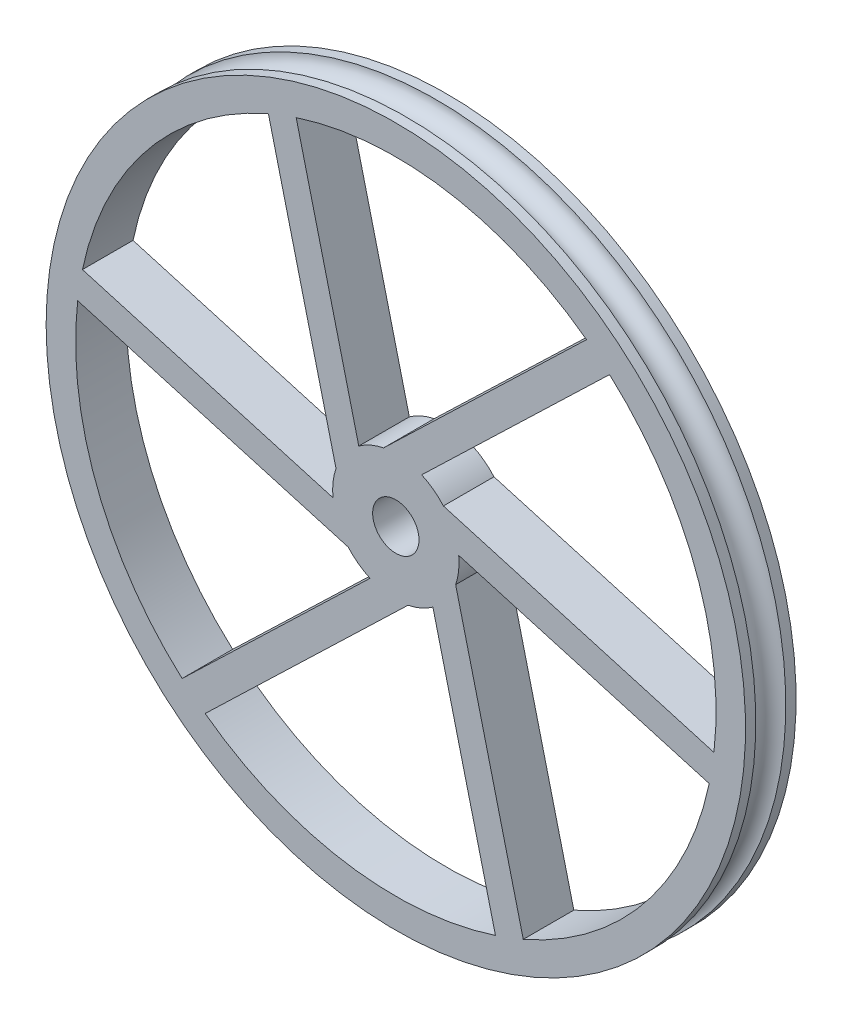
SolidWorks part; units mm, degrees
ref_plane "Front Plane" through (0, 0, 0) normal (0, 0, 1) x (1, 0, 0)
ref_plane "Top Plane" through (0, 0, 0) normal (0, 1, 0) x (1, 0, 0)
ref_plane "Right Plane" through (0, 0, 0) normal (1, 0, 0) x (0, 0, -1)
sketch "Sketch2" plane through (0, 0, 0) normal (0, 1, 0) x (1, 0, 0)
  line L0 (41.5, -1.78) -> (41.5, -3)
  line L1 (38, 3) -> (41.5, 3)
  line L2 (38, 3) -> (38, -3)
  line L3 (38, -3) -> (41.5, -3)
  line L4 (41.5, 3) -> (41.5, 1.78)
  line L5 (0, 19.9254) -> (0, -18.4403) construction
  arc A0 (41.5, 1.78) -> (41.5, -1.78) centre (41.5, 0) ccw
  point P4 (38, 0)
  dimension "D1" = 1.78
  dimension "D2" = 3.5
  dimension "D3" = 6
  dimension "D4" = 38
revolve "rim" add sketch "Sketch2" angle 360 about L5
sketch "Sketch3" plane through (0, 0, 0) normal (0, 0, 1) x (1, 0, 0)
  circle A0 centre (0, 0) radius 7.5
  dimension "D1" = 15
extrude "center" add sketch "Sketch3" along normal up to surface and the other way up to surface separate body up to face at (-41.5, 0, 3) other way up to face at (-38, 0, -3)
sketch "Sketch4" plane through (0, 0, 3) normal (0, 0, 1) x (1, 0, 0)
  line L0 (-1.4541, 7.3577) -> (23.0493, 30.9286)
  line L1 (23.0493, 30.9286) -> (25.4757, 28.4061)
  line L2 (25.4757, 28.4061) -> (3.0627, 6.8461)
  line L3 (-1.4541, 7.3577) -> (3.0627, 6.8461)
  line L4 (5.6449, 4.9381) -> (38.3095, -4.497)
  line L5 (38.3095, -4.497) -> (37.3383, -7.8595)
  line L6 (37.3383, -7.8595) -> (7.4603, 0.7707)
  line L7 (5.6449, 4.9381) -> (7.4603, 0.7707)
  line L8 (7.099, -2.4196) -> (15.2603, -35.4255)
  line L9 (15.2603, -35.4255) -> (11.8626, -36.2657)
  line L10 (11.8626, -36.2657) -> (4.3976, -6.0755)
  line L11 (7.099, -2.4196) -> (4.3976, -6.0755)
  line L12 (1.4541, -7.3577) -> (-23.0493, -30.9286)
  line L13 (-23.0493, -30.9286) -> (-25.4757, -28.4061)
  line L14 (-25.4757, -28.4061) -> (-3.0627, -6.8461)
  line L15 (1.4541, -7.3577) -> (-3.0627, -6.8461)
  line L16 (-5.6449, -4.9381) -> (-38.3095, 4.497)
  line L17 (-38.3095, 4.497) -> (-37.3383, 7.8595)
  line L18 (-37.3383, 7.8595) -> (-7.4603, -0.7707)
  line L19 (-5.6449, -4.9381) -> (-7.4603, -0.7707)
  line L20 (-7.099, 2.4196) -> (-15.2603, 35.4255)
  line L21 (-15.2603, 35.4255) -> (-11.8626, 36.2657)
  line L22 (-11.8626, 36.2657) -> (-4.3976, 6.0755)
  line L23 (-7.099, 2.4196) -> (-4.3976, 6.0755)
  circle A0 centre (0, 0) radius 7.5 construction
  point P30 (0, 0)
  dimension "D2" = 3.5
  dimension "D3" = 34
  dimension "D1" = 6
extrude "spokes" add sketch "Sketch4" against normal up to surface (6 mm away) up to face at (-38, 0, -3)
sketch "Sketch5" plane through (0, 0, 3) normal (0, 0, 1) x (1, 0, 0)
  circle A0 centre (0, 0) radius 2.75
  dimension "D1" = 5.5
extrude "hole" cut sketch "Sketch5" against normal up to surface (6 mm away) up to face at (1.3911, 21.1056, -3)
